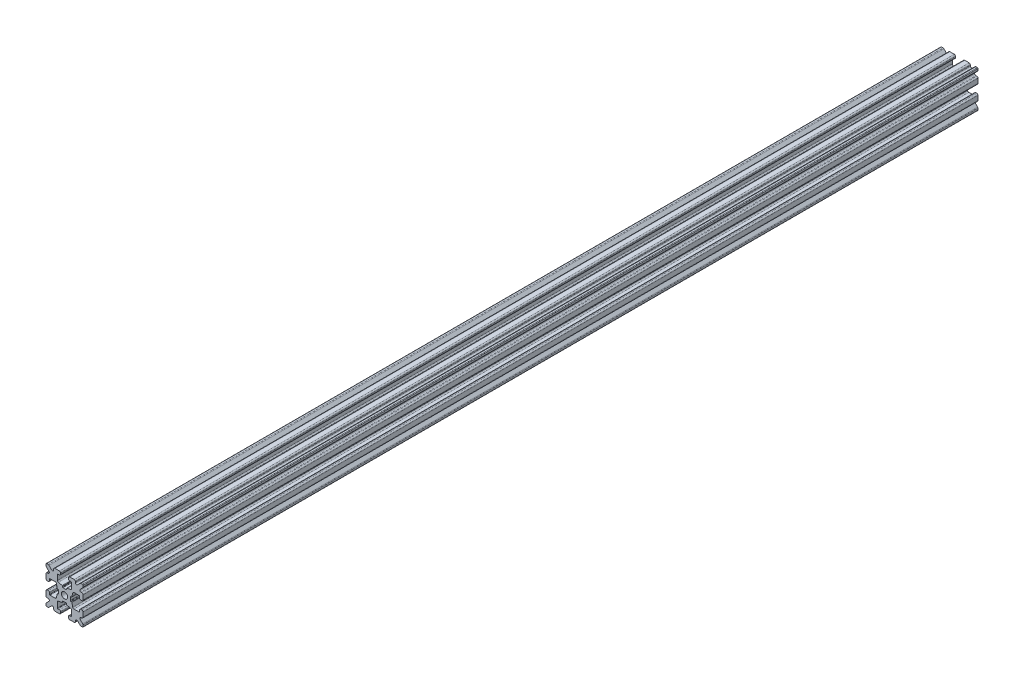
SolidWorks part; units mm, degrees
material "1060 Alloy"
ref_plane "Front Plane" through (0, 0, 0) normal (0, 0, 1) x (1, 0, 0)
ref_plane "Top Plane" through (0, 0, 0) normal (0, 1, 0) x (1, 0, 0)
ref_plane "Right Plane" through (0, 0, 0) normal (1, 0, 0) x (0, 0, -1)
sketch "Sketch1" plane through (0, 0, 0) normal (0, 0, 1) x (1, 0, 0)
  line L1 (-7.5, -7.5) -> (7.5, -7.5)
  line L2 (-7.5, -7.5) -> (-7.5, 7.5)
  line L3 (-7.5, 7.5) -> (7.5, 7.5)
  line L4 (7.5, -7.5) -> (7.5, 7.5)
  line L5 (-7.5, -7.5) -> (7.5, 7.5) construction
  line L6 (-7.5, 7.5) -> (7.5, -7.5) construction
  circle A0 centre (0, 0) radius 1.25
  point P0 (0, 0)
  dimension "D2" = 2.5
  dimension "D1" = 15
extrude "Boss-Extrude1" add sketch "Sketch1" along normal mid plane 362
fillet "Fillet1" radius 0.25 4 edges at (7.5, -7.5, 0) (-7.5, -7.5, 0) (7.5, 7.5, 0) (-7.5, 7.5, 0)
sketch "Sketch2" plane through (0, 0, 181) normal (0, 0, 1) x (1, 0, 0)
  line L0 (-7.5, 7.25) -> (-7.5, -7.25) construction
  line L1 (-7.5, 1.6) -> (-6.1, 1.6)
  line L2 (-7.5, 1.6) -> (-7.5, -1.6)
  line L3 (-7.5, -1.6) -> (-6.1, -1.6)
  line L4 (-6.1, 1.6) -> (-6.1, 2.9)
  line L5 (0, 0) -> (-12.1036, 0) construction
  line L6 (-6.1, -2.9) -> (-3.4, -2.9)
  line L7 (0, 0) -> (-7.25, 7.25) construction
  line L8 (-6.1, 2.9) -> (-3.4, 2.9)
  line L9 (-3.4, -2.9) -> (-3.4, 2.9)
  line L10 (55, 0) -> (-55, 0) construction
  line L11 (-6.1, -2.9) -> (-6.1, -1.6)
  line L12 (2.9, 6.1) -> (1.6, 6.1)
  line L13 (2.9, 3.4) -> (-2.9, 3.4)
  line L14 (-2.9, 6.1) -> (-2.9, 3.4)
  line L15 (2.9, 6.1) -> (2.9, 3.4)
  line L16 (-1.6, 6.1) -> (-2.9, 6.1)
  line L17 (1.6, 7.5) -> (1.6, 6.1)
  line L18 (-1.6, 7.5) -> (1.6, 7.5)
  line L19 (-1.6, 7.5) -> (-1.6, 6.1)
  line L20 (-1.6, -7.5) -> (-1.6, -6.1)
  line L21 (-1.6, -7.5) -> (1.6, -7.5)
  line L22 (1.6, -7.5) -> (1.6, -6.1)
  line L23 (-1.6, -6.1) -> (-2.9, -6.1)
  line L24 (2.9, -6.1) -> (2.9, -3.4)
  line L25 (-2.9, -6.1) -> (-2.9, -3.4)
  line L26 (2.9, -3.4) -> (-2.9, -3.4)
  line L27 (2.9, -6.1) -> (1.6, -6.1)
  line L28 (6.1, -2.9) -> (6.1, -1.6)
  line L29 (3.4, -2.9) -> (3.4, 2.9)
  line L30 (6.1, 2.9) -> (3.4, 2.9)
  line L31 (6.1, -2.9) -> (3.4, -2.9)
  line L32 (6.1, 1.6) -> (6.1, 2.9)
  line L33 (7.5, -1.6) -> (6.1, -1.6)
  line L34 (7.5, 1.6) -> (7.5, -1.6)
  line L35 (7.5, 1.6) -> (6.1, 1.6)
  dimension "D1" = 3.2
  dimension "D2" = 5.8
  dimension "D3" = 1.4
  dimension "D4" = 2.7
extrude "Cut-Extrude1" cut sketch "Sketch2" against normal through all
sketch "Sketch4" plane through (0, 0, 181) normal (0, 0, 1) x (1, 0, 0)
  line L0 (-3.4, 2.9) -> (-2.75, 0)
  line L1 (55, 0) -> (-55, 0) construction
  line L2 (-2.75, 0) -> (-3.4, -2.9)
  line L3 (-3.4, -2.9) -> (-3.4, 2.9) construction
  line L4 (-3.4, 2.9) -> (-3.4, -2.9)
  line L5 (-2.9, 3.4) -> (0, 2.75)
  line L6 (0, 2.75) -> (2.9, 3.4)
  line L7 (2.9, 3.4) -> (-2.9, 3.4)
  line L8 (3.4, 2.9) -> (2.75, 0)
  line L9 (2.75, 0) -> (3.4, -2.9)
  line L10 (3.4, -2.9) -> (3.4, 2.9)
  line L11 (-2.9, -3.4) -> (0, -2.75)
  line L12 (0, -2.75) -> (2.9, -3.4)
  line L13 (2.9, -3.4) -> (-2.9, -3.4)
  circle A2 centre (0, 0) radius 2.75
  circle A3 centre (0, 0) radius 2.75 construction
  dimension "D1" = 1.5
extrude "Cut-Extrude3" cut sketch "Sketch4" against normal through all
fillet "Fillet3" radius 0.5 16 edges at (-6.1, -1.6, 0) (-7.5, -1.6, 0) (-6.1, 1.6, 0) (-7.5, 1.6, 0) (-1.6, -7.5, 0) (-1.6, -6.1, 0) (1.6, -7.5, 0) (1.6, -6.1, 0) (6.1, -1.6, 0) (7.5, -1.6, 0) (7.5, 1.6, 0) (6.1, 1.6, 0) (1.6, 7.5, 0) (1.6, 6.1, 0) (-1.6, 7.5, 0) (-1.6, 6.1, 0)
fillet "Fillet4" radius 0.5 8 edges at (-3.4, 2.9, 0) (-3.4, -2.9, 0) (2.9, -3.4, 0) (-2.9, -3.4, 0) (3.4, -2.9, 0) (3.4, 2.9, 0) (-2.9, 3.4, 0) (2.9, 3.4, 0)
fillet "Fillet5" radius 3 4 edges at (0, -2.75, 0) (2.75, 0, 0) (-2.75, 0, 0) (0, 2.75, 0)
fillet "Fillet6" radius 0.2 8 edges at (-2.9, -6.1, 0) (2.9, -6.1, 0) (6.1, -2.9, 0) (6.1, 2.9, 0) (2.9, 6.1, 0) (-2.9, 6.1, 0) (-6.1, -2.9, 0) (-6.1, 2.9, 0)
sketch "Sketch5" plane through (0, 0, 181) normal (0, 0, 1) x (1, 0, 0)
  line L0 (0, 0) -> (-7.25, 7.25) construction
  line L1 (-7.5, 6.4393) -> (-5.4607, 4.4)
  line L2 (-6.4393, 7.5) -> (-4.4, 5.4607)
  line L3 (-7.5, 4.4) -> (-5.4607, 4.4)
  line L4 (-3.8003, 2.9) -> (-5.9, 2.9) construction
  line L5 (0, 0) -> (-12.1819, 0) construction
  line L6 (-4.4, 7.5) -> (-4.4, 5.4607)
  line L7 (-2.9, 5.9) -> (-2.9, 3.8003) construction
  line L8 (-7.5, 6.4393) -> (-7.5, 4.4)
  line L9 (-7.5, 7.25) -> (-7.5, 2.1) construction
  line L10 (2.1, -7.5) -> (7.25, -7.5) construction
  line L11 (7.5, -7.25) -> (7.5, -2.1) construction
  line L12 (7.25, 7.5) -> (2.1, 7.5) construction
  line L13 (-2.1, 7.5) -> (-7.25, 7.5) construction
  line L14 (-4.4, 7.5) -> (-6.4393, 7.5)
  line L16 (55, 0) -> (-55, 0) construction
  line L17 (0, 0) -> (0, 10.993) construction
  line L18 (0, -54.6431) -> (0, 54.6431) construction
  line L20 (4.4, 7.5) -> (6.4393, 7.5)
  line L22 (7.5, 6.4393) -> (7.5, 4.4)
  line L23 (4.4, 7.5) -> (4.4, 5.4607)
  line L24 (7.5, 4.4) -> (5.4607, 4.4)
  line L25 (6.4393, 7.5) -> (4.4, 5.4607)
  line L26 (7.5, 6.4393) -> (5.4607, 4.4)
  line L27 (7.5, -6.4393) -> (5.4607, -4.4)
  line L28 (6.4393, -7.5) -> (4.4, -5.4607)
  line L29 (7.5, -4.4) -> (5.4607, -4.4)
  line L30 (4.4, -7.5) -> (4.4, -5.4607)
  line L31 (7.5, -6.4393) -> (7.5, -4.4)
  line L33 (4.4, -7.5) -> (6.4393, -7.5)
  line L36 (-4.4, -7.5) -> (-6.4393, -7.5)
  line L38 (-7.5, -6.4393) -> (-7.5, -4.4)
  line L39 (-4.4, -7.5) -> (-4.4, -5.4607)
  line L40 (-7.5, -4.4) -> (-5.4607, -4.4)
  line L41 (-6.4393, -7.5) -> (-4.4, -5.4607)
  line L42 (-7.5, -6.4393) -> (-5.4607, -4.4)
  dimension "D1" = 1.5
  dimension "D2" = 1.5
  dimension "D3" = 1.5
extrude "Cut-Extrude4" cut sketch "Sketch5" against normal through all
fillet "Fillet8" radius 0.5 24 edges at (-5.4607, 4.4, 0) (-7.5, 4.4, 0) (-5.4607, -4.4, 0) (-7.5, -4.4, 0) (-4.4, -7.5, 0) (-4.4, -5.4607, 0) (4.4, -7.5, 0) (4.4, -5.4607, 0) (5.4607, -4.4, 0) (7.5, -4.4, 0) (7.5, 4.4, 0) (5.4607, 4.4, 0) (4.4, 5.4607, 0) (4.4, 7.5, 0) (-4.4, 5.4607, 0) (-4.4, 7.5, 0) (-6.4393, 7.5, 0) (-7.5, 6.4393, 0) (6.4393, 7.5, 0) (7.5, 6.4393, 0) (6.4393, -7.5, 0) (7.5, -6.4393, 0) (-6.4393, -7.5, 0) (-7.5, -6.4393, 0)
sketch "Sketch6" plane through (0, 0, 181) normal (0, 0, 1) x (1, 0, 0)
  line L0 (0, 0) -> (0, 11.013) construction
  line L1 (0.6561, 2.8971) -> (2.1235, 2.8971) construction
  line L2 (0, -54.6431) -> (0, 54.6431) construction
  line L3 (0, 0) -> (7.25, 7.25) construction
  line L4 (7.5, 0.8255) -> (7.5, -0.8255)
  line L5 (2.3471, 0.8255) -> (7.5, 0.8255)
  line L6 (0, 0) -> (12.4016, 0) construction
  line L7 (0.8255, -7.5) -> (-0.8255, -7.5)
  line L8 (2.3471, -0.8255) -> (2.3471, 0.8255)
  line L9 (0.8255, -2.3471) -> (0.8255, -7.5)
  line L10 (7.5, -0.8255) -> (2.3471, -0.8255)
  line L11 (-7.5, -0.8255) -> (-2.3471, -0.8255)
  line L12 (-2.3471, -0.8255) -> (-2.3471, 0.8255)
  line L13 (-0.8255, -2.3471) -> (0.8255, -2.3471)
  line L14 (-0.8255, 7.5) -> (-0.8255, 2.3471)
  line L15 (-0.8255, 2.3471) -> (0.8255, 2.3471)
  line L16 (-0.8255, -7.5) -> (-0.8255, -2.3471)
  line L17 (0.8255, 2.3471) -> (0.8255, 7.5)
  line L18 (0.8255, 7.5) -> (-0.8255, 7.5)
  line L19 (3.9, 7.5) -> (2.1, 7.5) construction
  line L20 (-2.3471, 0.8255) -> (-7.5, 0.8255)
  line L21 (-7.5, 0.8255) -> (-7.5, -0.8255)
  point P5 (0, -2.5973)
  point P7 (0, 2.5973)
  dimension "D3" = 0.55
  dimension "D1" = 1.651
extrude "Cut-Extrude5" cut sketch "Sketch6" against normal through all
fillet "Fillet10" radius 0.2 16 edges at (-2.935, 0.8255, 0) (-2.935, -0.8255, 0) (2.935, -0.8255, 0) (2.935, 0.8255, 0) (0.8255, 2.935, 0) (-0.8255, 2.935, 0) (-2.3471, 0.8255, 0) (-2.3471, -0.8255, 0) (0.8255, 2.3471, 0) (-0.8255, 2.3471, 0) (2.3471, 0.8255, 0) (2.3471, -0.8255, 0) (0.8255, -2.935, 0) (0.8255, -2.3471, 0) (-0.8255, -2.3471, 0) (-0.8255, -2.935, 0)
